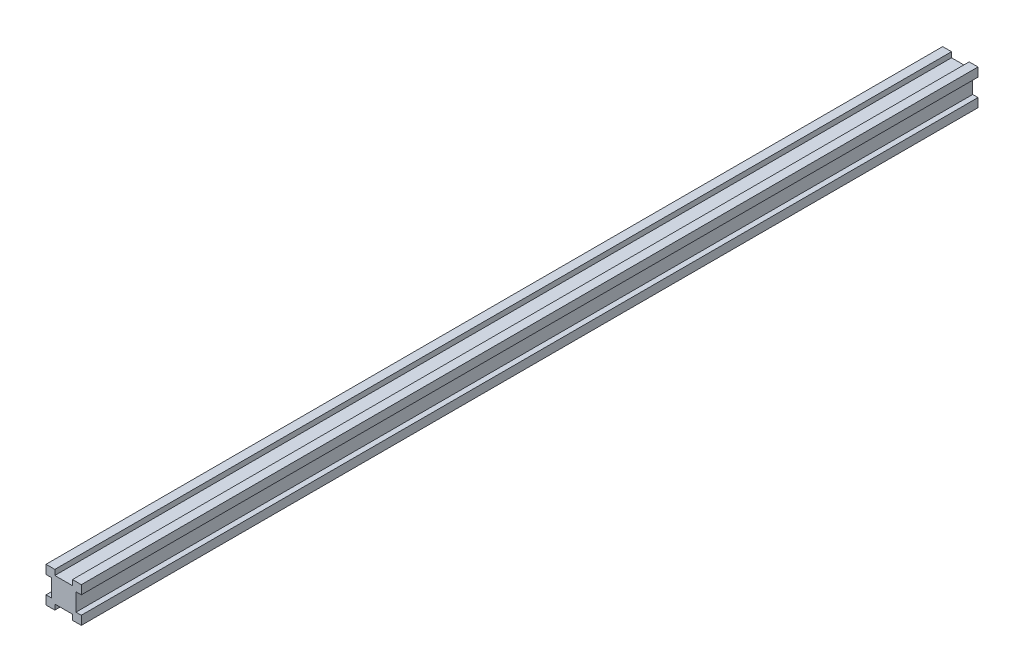
SolidWorks part; units mm, degrees
ref_plane "前视基准面" through (0, 0, 0) normal (0, 0, 1) x (1, 0, 0)
ref_plane "上视基准面" through (0, 0, 0) normal (0, 1, 0) x (1, 0, 0)
ref_plane "右视基准面" through (0, 0, 0) normal (1, 0, 0) x (0, 0, -1)
sketch "草图1" plane through (0, 0, 0) normal (0, 0, 1) x (1, 0, 0)
  line L0 (-5, 10) -> (-5, 7)
  line L1 (-10, -10) -> (10, -10)
  line L2 (-10, -10) -> (-10, -5)
  line L3 (-10, 10) -> (-5, 10)
  line L4 (10, -10) -> (10, -5)
  line L5 (-10, -10) -> (10, 10) construction
  line L6 (-10, 10) -> (10, -10) construction
  line L7 (-5, 7) -> (5, 7)
  line L8 (5, 7) -> (5, 10)
  line L9 (0, 0) -> (0, 17.8745) construction
  line L10 (7, 5) -> (7, -5)
  line L11 (10, 5) -> (7, 5)
  line L12 (7, -5) -> (10, -5)
  line L13 (5, -7) -> (-5, -7)
  line L14 (5, -10) -> (5, -7)
  line L15 (-5, -7) -> (-5, -10)
  line L16 (-7, -5) -> (-7, 5)
  line L17 (-10, -5) -> (-7, -5)
  line L18 (-7, 5) -> (-10, 5)
  line L19 (10, 5) -> (10, 10)
  line L20 (5, 10) -> (10, 10)
  line L21 (-10, 5) -> (-10, 10)
  point P0 (0, 0)
  point P27 (0, 0)
  dimension "D1" = 20
  dimension "D2" = 20
  dimension "D3" = 10
  dimension "D4" = 3
  dimension "D5" = 4
extrude "凸台-拉伸1" add sketch "草图1" along normal mid plane 508 contours L21 L18 L16 L17 L2 L1 L15 L13 L14 L4 L12 L10 L11 L19 L20 L8 L7 L0 L3
